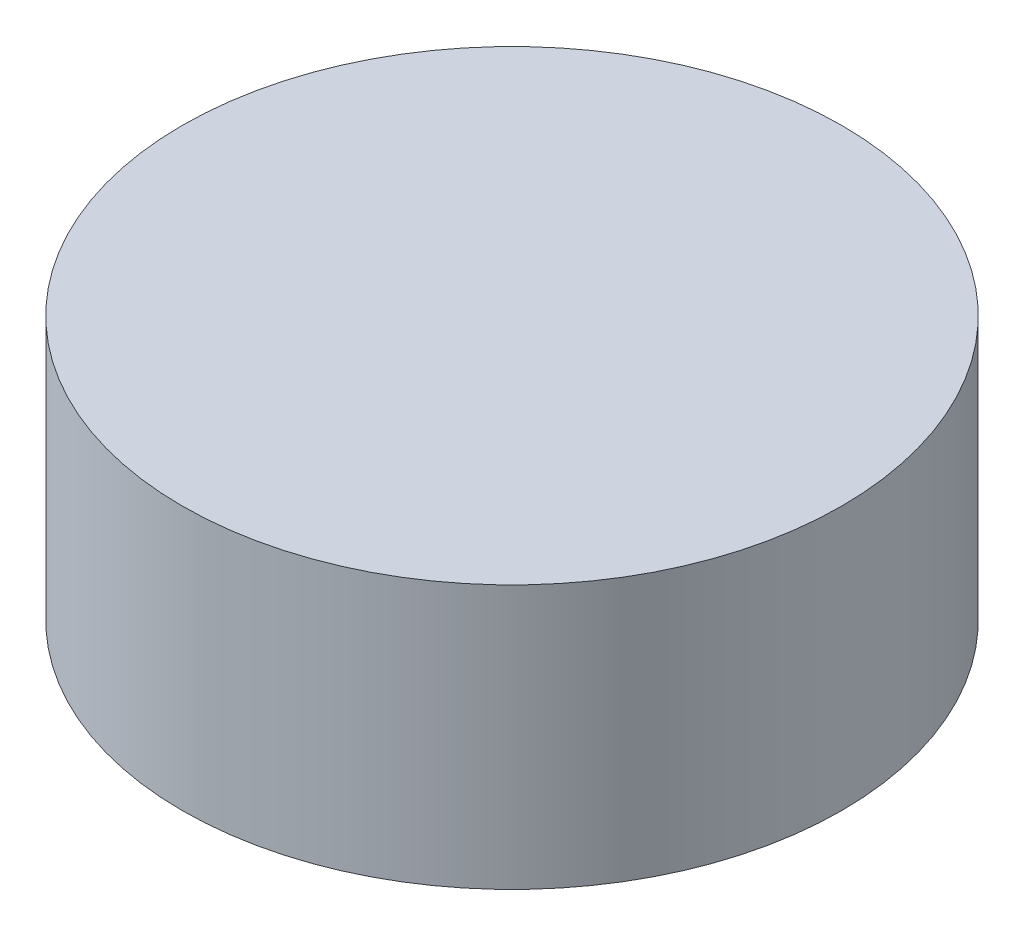
SolidWorks part; units mm, degrees
ref_plane "Front Plane" through (0, 0, 0) normal (0, 0, 1) x (1, 0, 0)
ref_plane "Top Plane" through (0, 0, 0) normal (0, 1, 0) x (1, 0, 0)
ref_plane "Right Plane" through (0, 0, 0) normal (1, 0, 0) x (0, 0, -1)
sketch "Sketch1" plane through (0, 0, 0) normal (0, 1, 0) x (1, 0, 0)
  circle A0 centre (0, 0) radius 32.75
  point P4 (0, 0)
  dimension "D1" = 65.5
extrude "Boss-Extrude1" add sketch "Sketch1" along normal blind 26.2
sketch "Sketch2" plane through (0, 0, 0) normal (0, -1, 0) x (1, 0, 0)
  point P0 (0, 0)
sketch "Sketch3" plane through (0, 0, 0) normal (0, -1, 0) x (1, 0, 0)
  circle A0 centre (0, 0) radius 22.75
  dimension "D1" = 45.5
extrude "Cut-Extrude1" cut sketch "Sketch3" against normal blind 8.4
sketch "Sketch4" plane through (0, 8.4, 0) normal (0, -1, 0) x (1, 0, 0)
  line L1 (-5.8514, -3.7096) -> (0.2869, -6.9223)
  line L2 (0.2869, -6.9223) -> (6.1383, -3.2127)
  line L3 (6.1383, -3.2127) -> (5.8514, 3.7096)
  line L4 (5.8514, 3.7096) -> (-0.2869, 6.9223)
  line L5 (-0.2869, 6.9223) -> (-6.1383, 3.2127)
  line L6 (-6.1383, 3.2127) -> (-5.8514, -3.7096)
  circle A0 centre (0, 0) radius 6 construction
  dimension "D1" = 12
extrude "Cut-Extrude2" cut sketch "Sketch4" against normal blind 4.5
equation "\"MDF\"= 4.8mm"
equation "\"Foamcore\"= 4.6mm"
equation "\"PCB\" = 1.6mm"
equation "\"GMaterial\"= \"MDF\""
equation "\"BaseWidth\" = 10in"
equation "\"SkidLength\" = 1in"
equation "\"SkidClearance\" = 0.4in"
equation "\"MotorMountLength\" = 2in"
equation "\"MotorMountWidth\" = \"GMaterial\""
equation "\"MotorMountHeight\" = 2.25in"
equation "\"UnoStackWidth\" = 77.4mm"
equation "\"UnoStackLength\" = 79.8mm"
equation "\"UnoStackHeight\" = 34.2mm"
equation "\"TallHexRiserHeight\" = 22.2mm"
equation "\"PingPongBallSize\" = 40mm"
equation "\"BarrelLength\" = 9in"
equation "\"BarrelSize\" = \"PingPongBallSize\""
equation "\"PlatformLength\" = 4in"
equation "\"PlatformWidth\" = 6in"
equation "\"D1@Boss-Extrude1\" = \"PitchingWheelWidth\""
equation "\"ServoMountHeight\"=2.49223"
equation "\"ServoGearHeight\" = 0.95330261in"
equation "\"ServoMountLength\"= 1.53774"
equation "\"PivotHoleRadius\"= 0.616358"
equation "\"PlatformMountHeight\" = 3.19"
equation "\"TensionOffSet\"= .3mm"
equation "\"MotorMountWedge\"=0.333333"
equation "\"LaserCutterOffset\"= .3mm"
equation "\"BumperWidth\"=11"
equation "\"PitchingWheelMountOffset\" = 8.4mm"
equation "\"PitchingWheelInnerDiameter\" = 45.5mm"
equation "\"PitchingWheelBoltShoulder\" = 4.5mm"
equation "\"BrassCouplingLength\" = 18mm"
equation "\"PitcherWheelCompression\" = 2.5mm"
equation "\"PitchingMotorHeight\" = 57.0mm"
equation "\"PitchingMotorShaftTopHeight\" = \"PitchingMotorHeight\" - 44.1mm"
equation "\"PitchingMotorBodyHeight\" = 38mm"
equation "\"PitchingMotorTopShoulderHeight\" = 40.6mm - \"PitchingMotorBodyHeight\" "
equation "\"PitchingMotorBottomShoulderHeight\" = 40.2mm - \"PitchingMotorBodyHeight\""
equation "\"PitchingMotorBottomShaftHeight\" = \"PitchingMotorHeight\" - \"PitchingMotorShaftTopHeight\" - \"PitchingMotorTopShoulderHeight\" - \"PitchingMotorBodyHeight\" - \"PitchingMotorBottomShoulderHeight\""
equation "\"PitchingMotorShaftDiameter\" = 2.2mm"
equation "\"PitchingMotorBodyDiameter\" = 27.4mm"
equation "\"PitchingMotorTopShoulderDiameter\" = 9.8mm"
equation "\"PitchingMotorBottomShoulderDiameter\" = 9.8mm"
equation "\"BrassCouplingHexSize\" = 12mm"
equation "\"BrassCouplingBoreSize\" = 3.17mm"
equation "\"D1@Sketch3\"=\"PitchingWheelInnerDiameter\""
equation "\"D1@Cut-Extrude1\"=\"PitchingWheelMountOffset\""
equation "\"D1@Sketch4\"=\"BrassCouplingHexSize\""
equation "\"D1@Cut-Extrude2\"=\"PitchingWheelBoltShoulder\""
equation "\"PitchingWheelWidth\" = 26.2mm"
equation "\"PitchingWheelDiameter\" = 65.5mm"
equation "\"PitchingMotorMountingHoleDistance\" = 16mm"
equation "\"PitchingMotorDistance\" = \"PitchingWheelDiameter\" + \"PingPongBallSize\" - \"PitcherWheelCompression\"*2"
equation "\"D1@Sketch1\"=\"PitchingWheelDiameter\""
